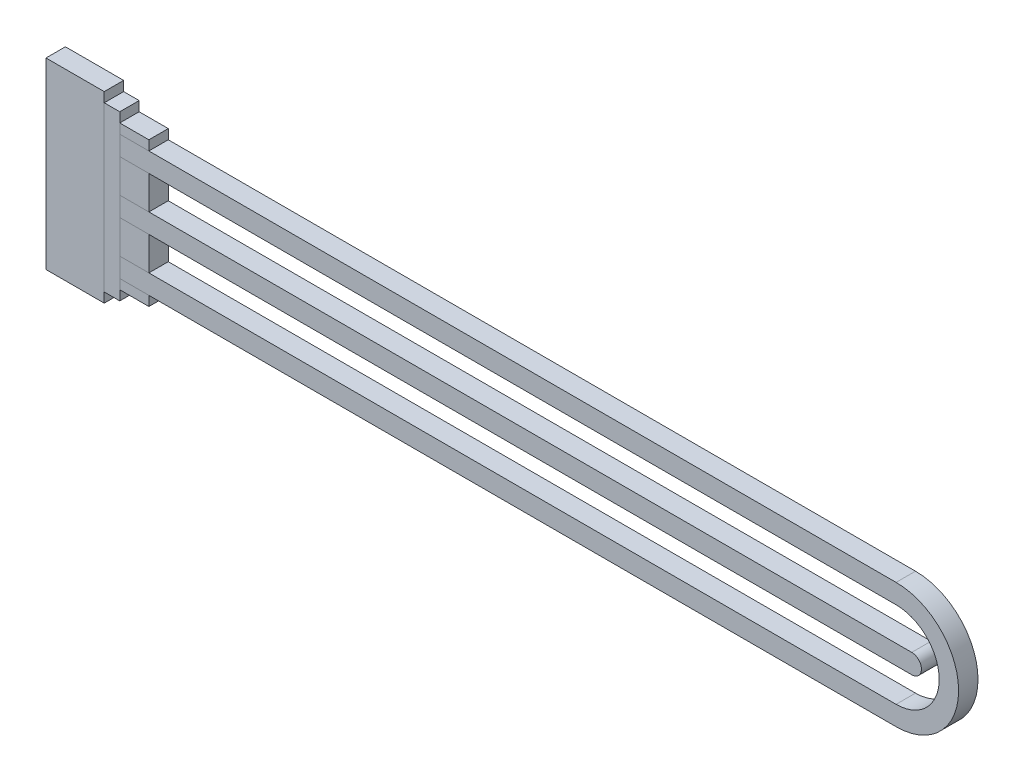
SolidWorks part; units mm, degrees
ref_plane "Alzado" through (0, 0, 0) normal (0, 0, 1) x (1, 0, 0)
ref_plane "Planta" through (0, 0, 0) normal (0, 1, 0) x (1, 0, 0)
ref_plane "Vista lateral" through (0, 0, 0) normal (1, 0, 0) x (0, 0, -1)
sketch "Sketch1" plane through (0, 0, 0) normal (0, 0, 1) x (1, 0, 0)
  line L0 (0, 0) -> (400, 0)
  line L1 (400, -64.4097) -> (0, -64.4097)
  line L2 (0, -10) -> (400, -10)
  line L3 (400, -54.4097) -> (0, -54.4097)
  line L4 (0, -10) -> (0, 0)
  line L5 (0, -54.4097) -> (0, -64.4097)
  line L6 (432.2048, -32.2048) -> (0, -32.2048) construction
  line L7 (0, -27.2048) -> (408.0642, -27.2048)
  line L8 (0, -27.2048) -> (0, -37.2048)
  line L9 (0, -37.2048) -> (408.0642, -37.2048)
  arc A0 (400, 0) -> (400, -64.4097) centre (400, -32.2048) cw
  arc A1 (400, -10) -> (400, -54.4097) centre (400, -32.2048) cw
  arc A4 (408.0642, -27.2048) -> (408.0642, -37.2048) centre (408.0642, -32.2048) cw
  point P9 (0, 0)
  point P16 (0, 0)
  dimension "D1" = 32.2048
  dimension "D3" = 10
  dimension "D2" = 400
  dimension "D4" = 5
extrude "Boss-Extrude1" add sketch "Sketch1" along normal blind 10
sketch "Sketch2" plane through (0, 0, 0) normal (-1, 0, 0) x (0, 0, 1)
  line L0 (5, 0) -> (5, -10) construction
  line L1 (10, 0) -> (0, 0) construction
  line L2 (10, -10) -> (0, -10) construction
  circle A0 centre (5, -4.907) radius 3
  dimension "D1" = 6
extrude "Boss-Extrude2" add sketch "Sketch2" along normal blind 15 separate body
sketch "Sketch3" plane through (0, 0, 0) normal (-1, 0, 0) x (0, 0, 1)
  line L0 (5, -54.4097) -> (5, -64.4097) construction
  line L1 (10, -54.4097) -> (0, -54.4097) construction
  line L2 (10, -64.4097) -> (0, -64.4097) construction
  circle A0 centre (5, -59.4097) radius 3
  dimension "D1" = 6
extrude "Boss-Extrude3" add sketch "Sketch3" along normal blind 15 separate body
sketch "Sketch4" plane through (0, 0, 0) normal (1, 0, 0) x (0, 0, -1)
  line L0 (-5, 0) -> (-5, -64.4097) construction
  line L1 (-10, 0) -> (0, 0) construction
  line L2 (-10, -64.4097) -> (0, -64.4097) construction
  line L3 (-10, -54.4097) -> (-10, -64.4097) construction
  line L4 (0, 5) -> (-10, 5)
  line L5 (0, 5) -> (0, -69.4097)
  line L6 (0, -69.4097) -> (-10, -69.4097)
  line L7 (-10, 5) -> (-10, -69.4097)
  line L8 (0, 5) -> (-10, -69.4097) construction
  line L9 (0, -69.4097) -> (-10, 5) construction
  line L10 (0, -32.2048) -> (-10, -32.2048) construction
  point P6 (-5, -32.2048)
  point P13 (-10, -59.4097)
  dimension "D1" = 5
extrude "Boss-Extrude4" add sketch "Sketch4" along normal blind 15 separate body
sketch "Sketch5" plane through (0, 0, 0) normal (-1, 0, 0) x (0, 0, 1)
  line L0 (5, 5) -> (5, -69.4097) construction
  line L1 (0, 5) -> (10, 5) construction
  line L2 (10, -69.4097) -> (0, -69.4097) construction
  line L3 (0, -32.2048) -> (10, -32.2048) construction
  line L4 (0, 10) -> (10, 10)
  line L5 (0, 10) -> (0, -74.4097)
  line L6 (0, -74.4097) -> (10, -74.4097)
  line L7 (10, 10) -> (10, -74.4097)
  line L8 (0, 10) -> (10, -74.4097) construction
  line L9 (0, -74.4097) -> (10, 10) construction
  line L12 (0, -54.4097) -> (0, -64.4097) construction
  point P6 (5, -32.2048)
  dimension "D1" = 5
extrude "Boss-Extrude5" add sketch "Sketch5" along normal blind 8 separate body
sketch "Sketch6" plane through (-8, 0, 0) normal (-1, 0, 0) x (0, 0, 1)
  line L0 (5, 10) -> (5, -74.4097) construction
  line L1 (10, 10) -> (0, 10) construction
  line L2 (0, -74.4097) -> (10, -74.4097) construction
  line L3 (10, -74.4097) -> (10, 10) construction
  line L4 (0, 15) -> (10, 15)
  line L5 (0, 15) -> (0, -79.4097)
  line L6 (0, -79.4097) -> (10, -79.4097)
  line L7 (10, 15) -> (10, -79.4097)
  line L8 (0, 15) -> (10, -79.4097) construction
  line L9 (0, -79.4097) -> (10, 15) construction
  line L10 (0, -32.2048) -> (10, -32.2048) construction
  point P6 (5, -32.2048)
  dimension "D1" = 5
extrude "Boss-Extrude6" add sketch "Sketch6" along normal blind 30 separate body
